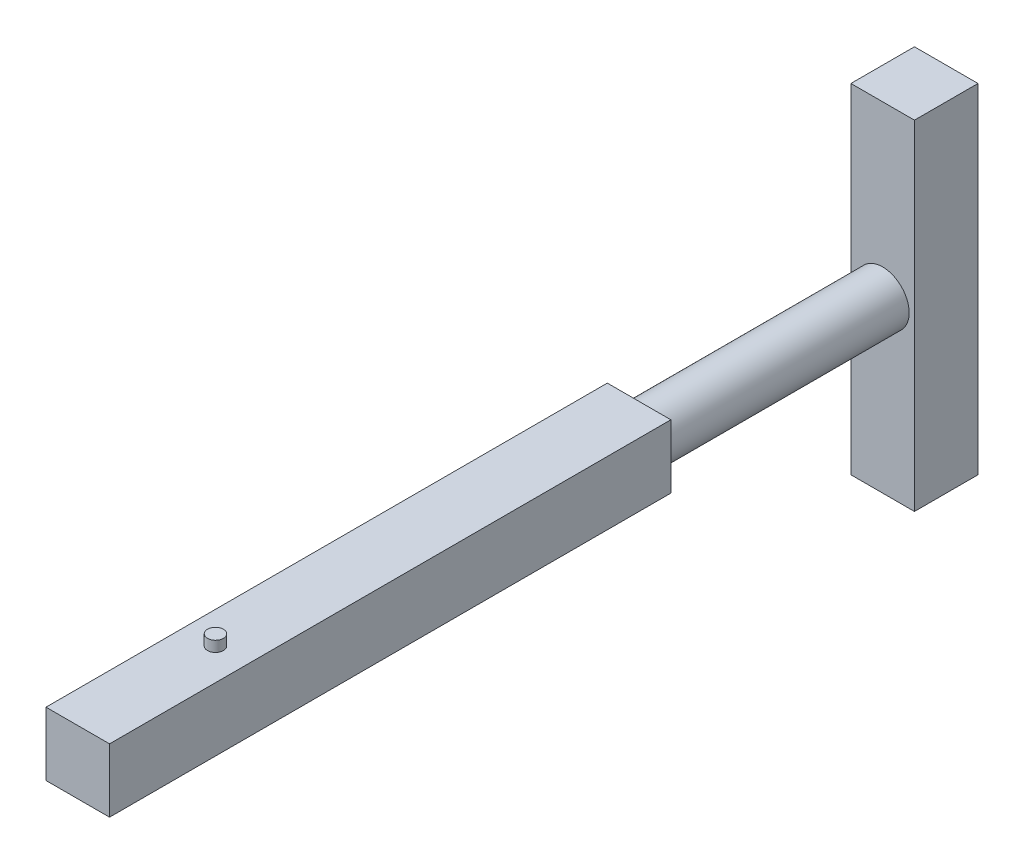
SolidWorks part; units mm, degrees
ref_plane "前视基准面" through (0, 0, 0) normal (0, 0, 1) x (1, 0, 0)
ref_plane "上视基准面" through (0, 0, 0) normal (0, 1, 0) x (1, 0, 0)
ref_plane "右视基准面" through (0, 0, 0) normal (1, 0, 0) x (0, 0, -1)
other "Configuration Table"
sketch "草图1" plane through (0, 0, 0) normal (0, 0, 1) x (1, 0, 0)
  line L1 (-30, 30) -> (30, 30)
  line L2 (-30, 30) -> (-30, -30)
  line L3 (-30, -30) -> (30, -30)
  line L4 (30, 30) -> (30, -30)
  line L5 (-30, 30) -> (30, -30) construction
  line L6 (-30, -30) -> (30, 30) construction
extrude "凸台-拉伸1" add sketch "草图1" along normal blind 530
sketch "草图2" plane through (0, 0, 0) normal (0, 0, -1) x (-1, 0, 0)
  circle A0 centre (0, 0) radius 25
extrude "凸台-拉伸2" add sketch "草图2" along normal blind 230
sketch "草图3" plane through (0, 30, 0) normal (0, 1, 0) x (1, 0, 0)
  line L0 (0, -530) -> (0, -400) construction
  line L1 (30, -530) -> (-30, -530) construction
  circle A0 centre (0, -400) radius 7.5
extrude "凸台-拉伸3" add sketch "草图3" along normal blind 10
sketch "草图4" plane through (0, -30, 0) normal (0, -1, 0) x (1, 0, 0)
  line L0 (0, 530) -> (0, 400) construction
  line L1 (-30, 530) -> (30, 530) construction
  circle A0 centre (0, 400) radius 7.5
extrude "凸台-拉伸4" add sketch "草图4" along normal blind 10
sketch "草图5" plane through (0, 0, -230) normal (0, 0, -1) x (-1, 0, 0)
  line L1 (-30, -160) -> (-30, 160)
  line L2 (-30, -160) -> (30, -160)
  line L3 (30, -160) -> (30, 160)
  line L4 (-30, 160) -> (30, 160)
  line L5 (-160, 30) -> (160, -30) construction
  line L6 (-160, -30) -> (160, 30) construction
  point P0 (0, 0)
extrude "凸台-拉伸5" add sketch "草图5" along normal blind 60
sketch "草图6" plane through (0, 0, -290) normal (0, 0, -1) x (-1, 0, 0)
  circle A0 centre (0, 0) radius 7.5
extrude "切除-拉伸1" cut sketch "草图6" against normal blind 40
